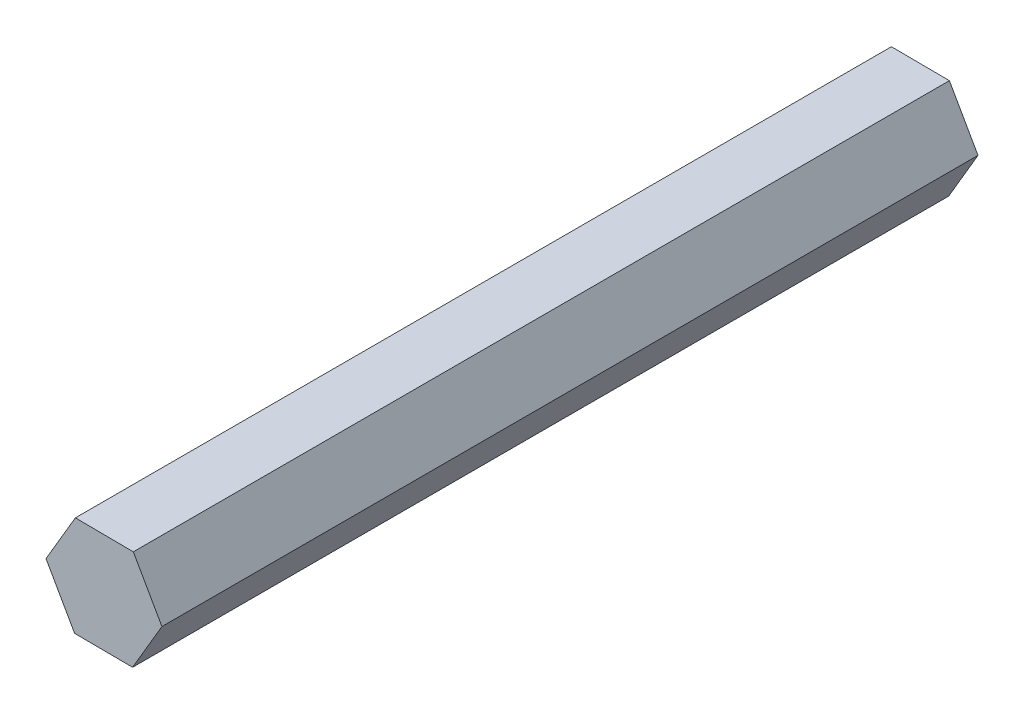
SolidWorks part; units mm, degrees
ref_plane "Front Plane" through (0, 0, 0) normal (0, 0, 1) x (1, 0, 0)
ref_plane "Top Plane" through (0, 0, 0) normal (0, 1, 0) x (1, 0, 0)
ref_plane "Right Plane" through (0, 0, 0) normal (1, 0, 0) x (0, 0, -1)
sketch "Sketch1" plane through (0, 0, 0) normal (0, 0, 1) x (1, 0, 0)
  line L1 (-1.4247, 2.5107) -> (-2.8867, 0.0215)
  line L2 (-2.8867, 0.0215) -> (-1.4619, -2.4892)
  line L3 (-1.4619, -2.4892) -> (1.4247, -2.5107)
  line L4 (1.4247, -2.5107) -> (2.8867, -0.0215)
  line L5 (2.8867, -0.0215) -> (1.4619, 2.4892)
  line L6 (1.4619, 2.4892) -> (-1.4247, 2.5107)
  circle A0 centre (0, 0) radius 2.5 construction
  dimension "D1" = 5
extrude "Boss-Extrude1" add sketch "Sketch1" along normal blind 40.64
